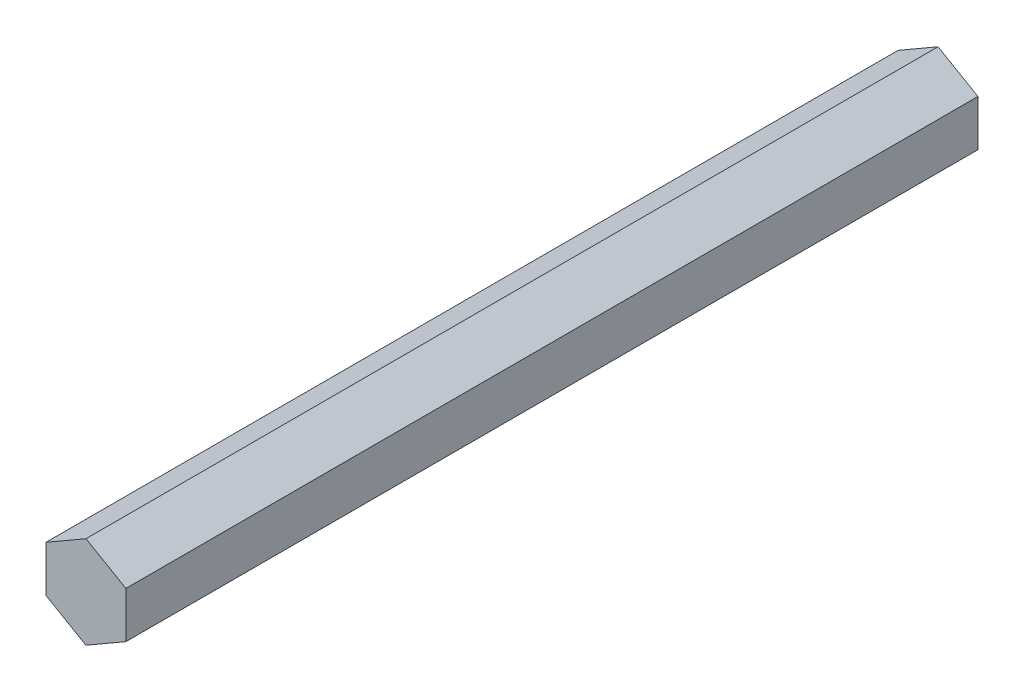
SolidWorks part; units mm, degrees
ref_plane "Front Plane" through (0, 0, 0) normal (0, 0, 1) x (1, 0, 0)
ref_plane "Top Plane" through (0, 0, 0) normal (0, 1, 0) x (1, 0, 0)
ref_plane "Right Plane" through (0, 0, 0) normal (1, 0, 0) x (0, 0, -1)
sketch "Sketch1" plane through (0, 0, 0) normal (0, 0, 1) x (1, 0, 0)
  line L1 (-4.7625, 0) -> (4.7625, 0) construction
  dimension "Width" = 9.525
sketch "Sketch2" plane through (0, 0, 0) normal (1, 0, 0) x (0, 0, -1)
  line L0 (50.8, 0) -> (-50.8, 0)
  point P4 (0, 0)
  dimension "Length" = 101.6
sketch "Sketch3" plane through (0, 0, 0) normal (0, 0, 1) x (1, 0, 0)
  line L1 (0, 5.4993) -> (-4.7625, 2.7496)
  line L2 (-4.7625, 2.7496) -> (-4.7625, -2.7496)
  line L3 (-4.7625, -2.7496) -> (0, -5.4993)
  line L4 (0, -5.4993) -> (4.7625, -2.7496)
  line L5 (4.7625, -2.7496) -> (4.7625, 2.7496)
  line L6 (4.7625, 2.7496) -> (0, 5.4993)
  circle A1 centre (0, 0) radius 4.7625 construction
extrude "Boss-Extrude1" add sketch "Sketch3" along normal up to vertex (50.8 mm away) and the other way up to vertex (50.8 mm away) up to point (0, 0, 50.8) other way up to point (0, 0, -50.8)
